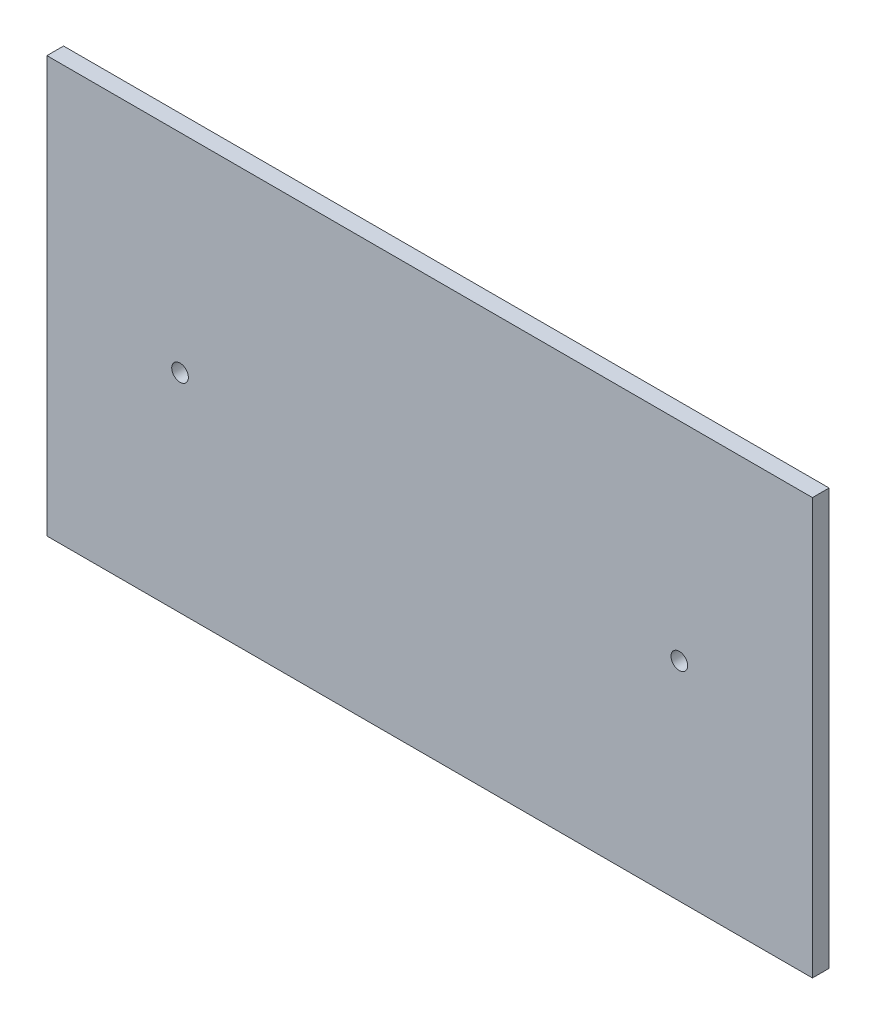
SolidWorks part; units mm, degrees
ref_plane "Vorne" through (0, 0, 0) normal (0, 0, 1) x (1, 0, 0)
ref_plane "Oben" through (0, 0, 0) normal (0, 1, 0) x (1, 0, 0)
ref_plane "Rechts" through (0, 0, 0) normal (1, 0, 0) x (0, 0, -1)
ref_plane "E_Boden" through (0, 1, 0) normal (0, 1, 0) x (1, 0, 0)
sketch "Skizze1" plane through (0, 0, 0) normal (0, 0, 1) x (1, 0, 0)
  line L0 (0, -137.0639) -> (0, 186.1997) construction
  line L1 (-325.7662, 0) -> (358.6205, 0) construction
  line L2 (-230, 125) -> (230, 125)
  line L3 (-230, 125) -> (-230, -125)
  line L4 (-230, -125) -> (230, -125)
  line L5 (230, 125) -> (230, -125)
  circle A0 centre (-150, 0) radius 5
  circle A1 centre (150, 0) radius 5
  point P21 (0, 0)
  dimension "D8" = 10
  dimension "D9" = 10
  dimension "D1" = 250
  dimension "D2" = 460
  dimension "D6" = 300
extrude "Aufsatz-Linear austragen1" add sketch "Skizze1" along normal blind 10
sketch "Skizze2" plane through (0, 0, 10) normal (0, 0, 1) x (1, 0, 0)
  line L0 (0, 89.2122) -> (0, -82.0073) construction
  line L1 (-210, 45) -> (-90, 45)
  line L2 (-210, 45) -> (-210, -45)
  line L3 (-210, -45) -> (-90, -45)
  line L4 (-90, 45) -> (-90, -45)
  line L5 (90, 45) -> (210, 45)
  line L6 (90, 45) -> (90, -45)
  line L7 (90, -45) -> (210, -45)
  line L8 (210, 45) -> (210, -45)
  line L9 (-248.4473, 0) -> (282.1176, 0) construction
  dimension "D1" = 120
  dimension "D2" = 120
  dimension "D3" = 180
  dimension "D4" = 90
  dimension "D5" = 90
